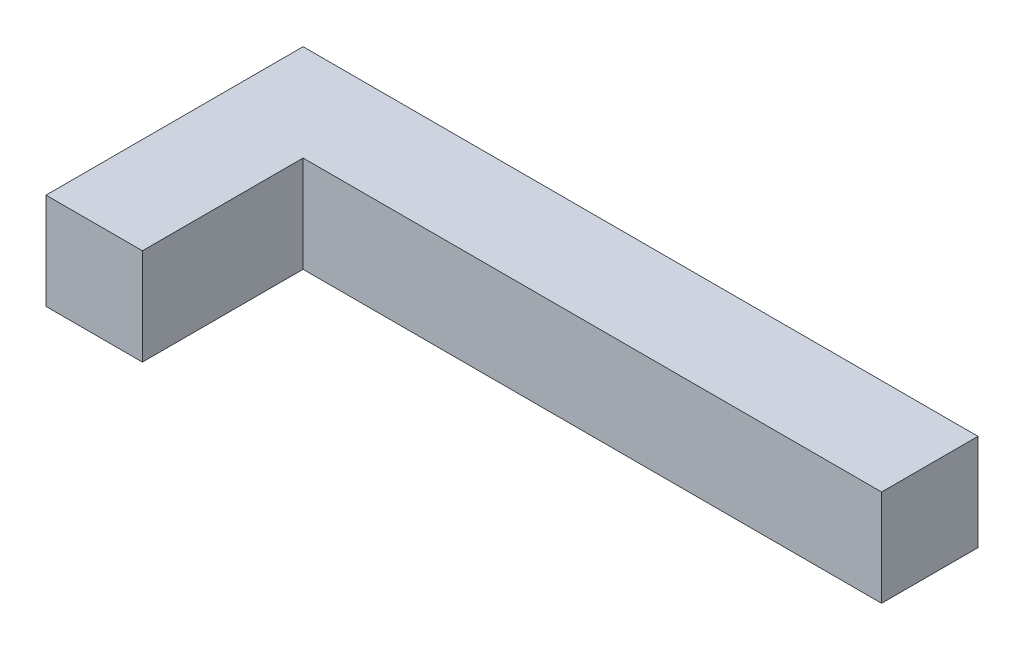
SolidWorks part; units mm, degrees
ref_plane "Plano frontal" through (0, 0, 0) normal (0, 0, 1) x (1, 0, 0)
ref_plane "Plano superior" through (0, 0, 0) normal (0, 1, 0) x (1, 0, 0)
ref_plane "Plano direito" through (0, 0, 0) normal (1, 0, 0) x (0, 0, -1)
sketch "Esboço1" plane through (0, 0, 0) normal (0, 0, 1) x (1, 0, 0)
  line L1 (0, 0) -> (15, 0)
  line L2 (0, 0) -> (0, -15)
  line L3 (0, -15) -> (15, -15)
  line L4 (15, 0) -> (15, -15)
extrude "Ressalto-extrusão1" add sketch "Esboço1" along normal blind 40
sketch "Esboço2" plane through (15, 0, 0) normal (1, 0, 0) x (0, 0, -1)
  line L0 (-40, -15) -> (0, -15) construction
  line L1 (0, 0) -> (-15, 0)
  line L2 (0, 0) -> (0, -15)
  line L3 (0, -15) -> (-15, -15)
  line L4 (-15, 0) -> (-15, -15)
extrude "Ressalto-extrusão2" add sketch "Esboço2" along normal blind 90
